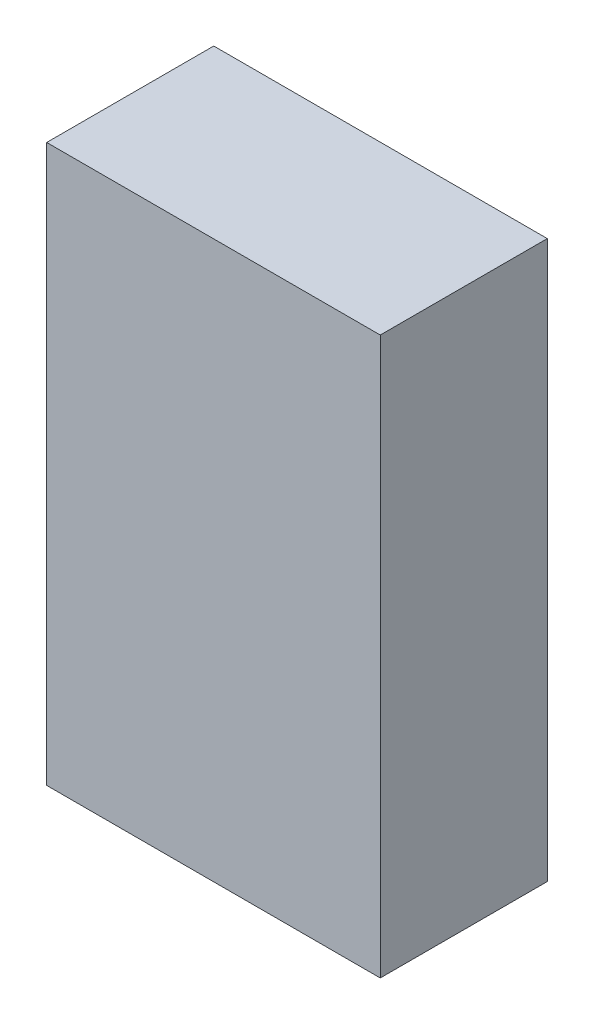
SolidWorks part; units mm, degrees
material "Polyurethane Foam Rigid"
ref_plane "X-Y Datum" through (0, 0, 0) normal (0, 0, 1) x (1, 0, 0)
ref_plane "X-Z Datum" through (0, 0, 0) normal (0, 1, 0) x (1, 0, 0)
ref_plane "Y-Z Datum" through (0, 0, 0) normal (1, 0, 0) x (0, 0, -1)
sketch "Sketch1" plane through (0, 0, 0) normal (0, 0, 1) x (1, 0, 0)
  line L1 (-38.0378, -63.5) -> (38.0378, -63.5)
  line L2 (-38.0378, -63.5) -> (-38.0378, 63.5)
  line L3 (-38.0378, 63.5) -> (38.0378, 63.5)
  line L4 (38.0378, -63.5) -> (38.0378, 63.5)
  line L5 (-38.0378, -63.5) -> (38.0378, 63.5) construction
  line L6 (-38.0378, 63.5) -> (38.0378, -63.5) construction
  point P0 (0, 0)
  dimension "D1" = 76.0755
  dimension "D2" = 127
extrude "Boss-Extrude1" add sketch "Sketch1" along normal blind 38.1
